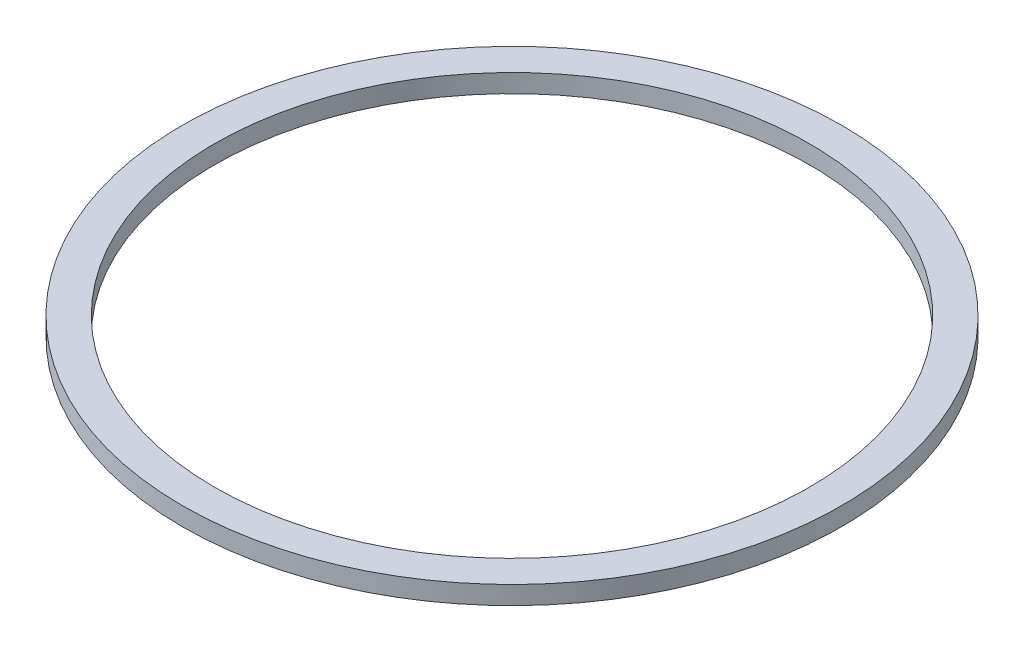
SolidWorks part; units mm, degrees
material "Pine"
ref_plane "Front Plane" through (0, 0, 0) normal (0, 0, 1) x (1, 0, 0)
ref_plane "Top Plane" through (0, 0, 0) normal (0, 1, 0) x (1, 0, 0)
ref_plane "Right Plane" through (0, 0, 0) normal (1, 0, 0) x (0, 0, -1)
sketch "Sketch1" plane through (0, 0, 0) normal (0, 1, 0) x (1, 0, 0)
  circle A0 centre (0, 0) radius 180
  circle A1 centre (0, 0) radius 162.5
  dimension "D1" = 360
  dimension "D2" = 325
extrude "Boss-Extrude1" add sketch "Sketch1" along normal mid plane 10
